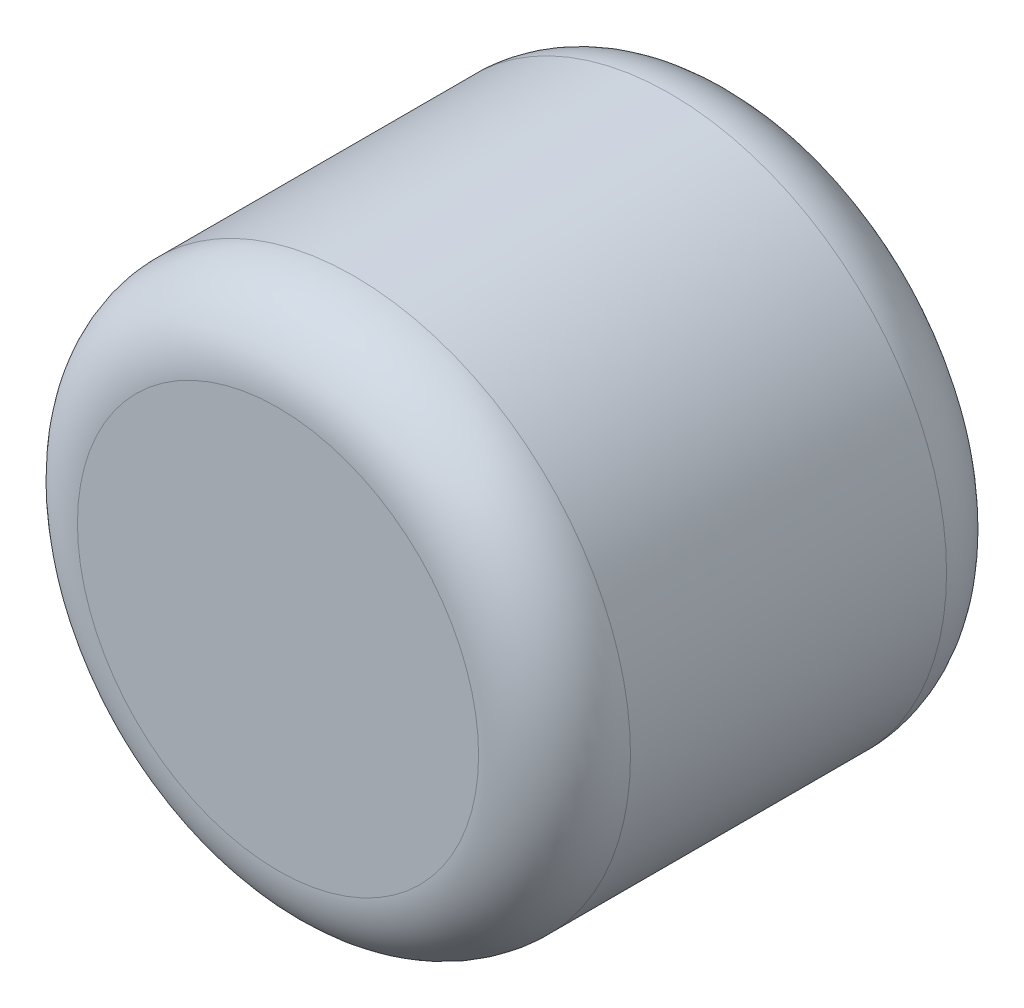
SolidWorks part; units mm, degrees
ref_plane "Front Plane" through (0, 0, 0) normal (0, 0, 1) x (1, 0, 0)
ref_plane "Top Plane" through (0, 0, 0) normal (0, 1, 0) x (1, 0, 0)
ref_plane "Right Plane" through (0, 0, 0) normal (1, 0, 0) x (0, 0, -1)
sketch "Sketch1" plane through (0, 0, 0) normal (0, 0, 1) x (1, 0, 0)
  circle A0 centre (0, 0) radius 4.6228
  dimension "D1" = 9.2456
extrude "Boss-Extrude1" add sketch "Sketch1" along normal blind 7.8232
fillet "Fillet1" radius 1.27 2 edges at (4.6228, 0, 0) (4.6228, 0, 7.8232)
